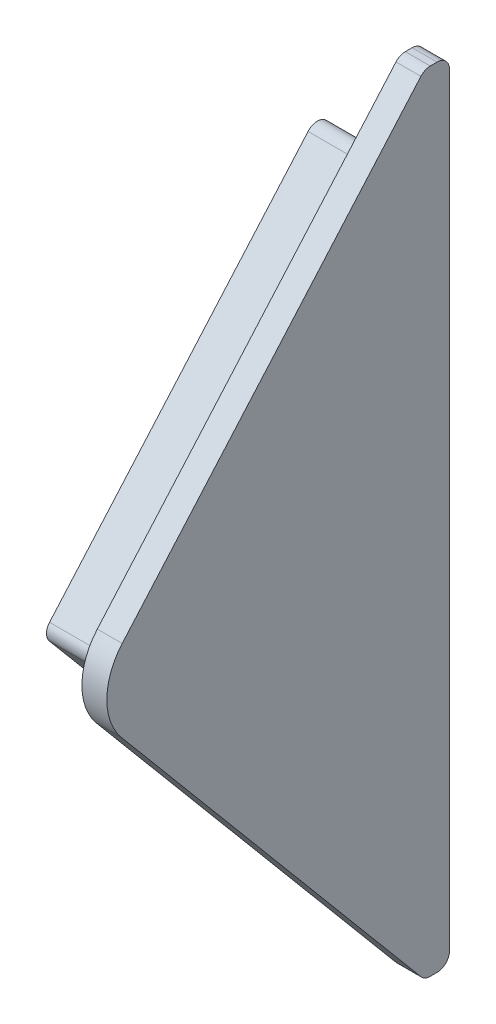
SolidWorks part; units mm, degrees
ref_plane "Front Plane" through (0, 0, 0) normal (0, 0, 1) x (1, 0, 0)
ref_plane "Top Plane" through (0, 0, 0) normal (0, 1, 0) x (1, 0, 0)
ref_plane "Right Plane" through (0, 0, 0) normal (1, 0, 0) x (0, 0, -1)
sketch "SideScreenView" plane through (0, 0, 0) normal (1, 0, 0) x (0, 0, -1)
  line L0 (0, 0) -> (0, 63.28)
  line L1 (0, 63.28) -> (21.5, 63.28)
  line L2 (21.5, 63.28) -> (21.5, 0)
  line L3 (21.5, 0) -> (0, 0)
  line L4 (0, 63.28) -> (-27.0861, 32.28)
  line L6 (18.75, 59.86) -> (15, 59.86)
  line L7 (15, 59.86) -> (15, 4.7)
  line L8 (15, 4.7) -> (18.75, 4.7)
  line L9 (18.75, 4.7) -> (18.75, 59.86)
  line L10 (11, 56.56) -> (15, 56.56)
  line L11 (15, 56.56) -> (15, 53.56)
  line L12 (15, 53.56) -> (11, 53.56)
  line L13 (11, 55.06) -> (11, 59.86) construction
  line L14 (11, 11) -> (15, 11)
  line L15 (15, 11) -> (15, 8)
  line L16 (15, 8) -> (11, 8)
  line L17 (11, 9.5) -> (11, 4.7) construction
  line L18 (11, 11) -> (11, 8)
  line L19 (11, 56.56) -> (11, 53.56)
  line L20 (15, 59.86) -> (11, 59.86) construction
  line L21 (18.75, 62.78) -> (21.5, 62.78)
  line L22 (21.5, 62.78) -> (21.5, 1.78)
  line L23 (21.5, 1.78) -> (18.75, 1.78)
  line L24 (18.75, 1.78) -> (18.75, 62.78)
  line L25 (11, 4.7) -> (15, 4.7) construction
  line L27 (-27.0861, 32.28) -> (0, 0)
  line L28 (1.5061, 61.9641) -> (-24.4532, 32.2537)
  line L29 (-24.4532, 32.2537) -> (1.5321, 1.2856)
  line L30 (11, 56.56) -> (0, 56.56) construction
  line L31 (11, 53.56) -> (0, 53.56) construction
  line L32 (11, 11) -> (0, 11) construction
  line L33 (11, 8) -> (0, 8) construction
  line L34 (0, 36.28) -> (4, 36.28)
  line L35 (0, 36.28) -> (0, 28.28)
  line L36 (4, 36.28) -> (4, 28.28)
  line L37 (0, 28.28) -> (4, 28.28)
  line L38 (0, 32.28) -> (15, 32.28) construction
  line L39 (4, 28.28) -> (4, 11) construction
  line L40 (4, 21.78) -> (9, 21.78)
  line L41 (4, 21.78) -> (4, 42.78)
  line L42 (9, 21.78) -> (9, 42.78)
  line L43 (4, 42.78) -> (9, 42.78)
  line L44 (4, 21.78) -> (9, 42.78) construction
  line L45 (9, 21.78) -> (4, 42.78) construction
  line L46 (4, 36.28) -> (9, 36.28)
  line L47 (9, 36.28) -> (9, 28.28)
  line L48 (9, 28.28) -> (4, 28.28)
  line L49 (9, 42.78) -> (9, 53.56) construction
  line L52 (0, 0) -> (21.5, 0)
  point P26 (18.75, 32.28)
  point P28 (18.75, 32.28)
  point P39 (6.5, 32.28)
  dimension "D3" = 55.16
  dimension "D4" = 3
  dimension "D5" = 4.8
  dimension "D6" = 4
  dimension "D7" = 61
  dimension "D8" = 6.5
  dimension "D9" = 8
  dimension "ThisArbitrary" = 2.75
  dimension "D10" = 4
  dimension "D11" = 40
  dimension "D12" = 8
  dimension "D13" = 2
  dimension "D14" = 2
  dimension "D16" = 0.5
  dimension "D19" = 21
  dimension "D20" = 15.3379
  dimension "D21" = 5
sketch "SideButtonView" plane through (0, 0, 0) normal (1, 0, 0) x (0, 0, -1)
  line L0 (21.5, 0) -> (0, 0) construction
  line L1 (0, 0) -> (0, 63.28) construction
  line L2 (0, 63.28) -> (21.5, 63.28) construction
  line L3 (21.5, 63.28) -> (21.5, 0) construction
  line L4 (21.5, 0) -> (0, 0)
  line L5 (0, 0) -> (0, 63.28)
  line L6 (0, 63.28) -> (21.5, 63.28)
  line L7 (21.5, 63.28) -> (21.5, 0)
  line L8 (15.7, 48.89) -> (30.7, 48.89)
  line L9 (30.7, 48.89) -> (30.7, 14.39)
  line L10 (30.7, 14.39) -> (15.7, 14.39)
  line L11 (15.7, 14.39) -> (15.7, 48.89)
  line L12 (15.7, 30.14) -> (15.7, 33.14)
  line L13 (15.7, 30.14) -> (11.2, 30.14)
  line L14 (15.7, 33.14) -> (11.2, 33.14)
  line L15 (11.2, 30.14) -> (11.2, 33.14)
  line L16 (11.2, 33.14) -> (30.7, 33.14) construction
  line L17 (11.2, 30.14) -> (11.2, 33.14)
  line L18 (11.2, 30.14) -> (9.5, 30.14)
  line L19 (11.2, 33.14) -> (9.5, 33.14)
  line L20 (9.5, 30.14) -> (9.5, 33.14)
  line L21 (6, 48.14) -> (9.5, 48.14)
  line L22 (6, 48.14) -> (6, 15.14)
  line L23 (9.5, 48.14) -> (9.5, 15.14)
  line L24 (6, 15.14) -> (9.5, 15.14)
  line L25 (6, 21.14) -> (6, 18.14)
  line L26 (6, 21.14) -> (2.5, 21.14)
  line L27 (6, 18.14) -> (2.5, 18.14)
  line L28 (2.5, 21.14) -> (2.5, 18.14)
  line L29 (6, 42.14) -> (6, 45.14)
  line L30 (6, 42.14) -> (2.5, 42.14)
  line L31 (6, 45.14) -> (2.5, 45.14)
  line L32 (2.5, 42.14) -> (2.5, 45.14)
  line L33 (2.5, 18.14) -> (9.5, 18.14) construction
  line L34 (2.5, 43.64) -> (2.5, 19.64) construction
  line L35 (6, 31.64) -> (2.5, 31.64) construction
  line L36 (2.5, 31.64) -> (0, 31.64) construction
  point P6 (9.5, 31.64)
  point P11 (15.7, 31.64)
  point P12 (9.5, 31.64)
  point P14 (15.7, 31.64)
  point P18 (11.2, 31.64)
  point P22 (11.2, 31.64)
  point P38 (2.5, 31.64)
  dimension "D1" = 34.5
  dimension "D2" = 15
  dimension "D3" = 19.5
  dimension "D4" = 7
  dimension "D5" = 8.7
  dimension "D6" = 24
  dimension "D7" = 3
  dimension "D8" = 2.5
  dimension "D9" = 3
  dimension "D10" = 3.5
  dimension "D11" = 33
sketch "Sketch3" plane through (0, 0, 0) normal (0, 1, 0) x (1, 0, 0)
  line L0 (-2, 21.5) -> (0, 21.5)
  dimension "D1" = 2
ref_plane "Plane1" through (0, 0, -21.5) normal (0, 0, 1) x (1, 0, 0)
sketch "FrontView" plane through (0, 0, -21.5) normal (0, 0, 1) x (1, 0, 0)
  line L0 (0, 63.28) -> (0, 0)
  line L1 (0, 63.28) -> (-133.94, 63.28)
  line L2 (0, 0) -> (-133.94, 0)
  line L3 (-133.94, 63.28) -> (-133.94, 0)
  line L4 (-0.5, 62.78) -> (-92.94, 62.78)
  line L5 (-0.5, 62.78) -> (-0.5, 1.78)
  line L6 (-92.94, 62.78) -> (-92.94, 1.78)
  line L7 (-0.5, 1.78) -> (-92.94, 1.78)
  line L8 (-15.882, 51.878) -> (-15.882, 12.682)
  line L9 (-7.9, 59.86) -> (-91.34, 59.86)
  line L10 (-7.9, 59.86) -> (-7.9, 4.7)
  line L11 (-7.9, 4.7) -> (-91.34, 4.7)
  line L12 (-91.34, 59.86) -> (-91.34, 4.7)
  line L17 (-15.882, 12.682) -> (-83.358, 12.682)
  line L18 (-83.358, 51.878) -> (-83.358, 12.682)
  line L19 (-15.882, 51.878) -> (-83.358, 51.878)
  line L20 (-97.94, 15.14) -> (-130.94, 48.14) construction
  line L21 (-97.94, 48.14) -> (-130.94, 48.14)
  line L22 (-97.94, 48.14) -> (-97.94, 15.14)
  line L23 (-97.94, 15.14) -> (-130.94, 15.14)
  line L24 (-130.94, 48.14) -> (-130.94, 15.14)
  line L25 (-126.44, 19.64) -> (-102.44, 43.64) construction
  line L26 (-133.94, 41.64) -> (-130.94, 41.64) construction
  line L27 (-133.94, 21.64) -> (-130.94, 21.64) construction
  line L28 (-133.94, 41.64) -> (-133.94, 21.64) construction
  line L49 (-86.12, 42.78) -> (-13.12, 42.78) construction
  line L50 (-86.12, 42.78) -> (-86.12, 21.78) construction
  line L51 (-13.12, 42.78) -> (-13.12, 21.78) construction
  line L52 (-86.12, 21.78) -> (-13.12, 21.78) construction
  line L53 (-49.62, 12.682) -> (-49.62, 21.78) construction
  line L54 (-13.12, 27.81) -> (0, 27.81)
  line L55 (-13.12, 27.81) -> (-13.12, 36.75)
  line L56 (-13.12, 36.75) -> (0, 36.75)
  line L57 (0, 27.81) -> (0, 36.75)
  line L58 (-88.12, 44.78) -> (-11.12, 44.78)
  line L59 (-11.12, 44.78) -> (-11.12, 19.78)
  line L60 (-88.12, 19.78) -> (-11.12, 19.78)
  line L61 (-88.12, 44.78) -> (-88.12, 19.78)
  line L62 (-97.94, 41.64) -> (-91.34, 41.64)
  line L63 (-97.94, 21.64) -> (-91.34, 21.64)
  line L70 (-117.44, 27.64) -> (-117.44, 35.64)
  line L71 (-117.44, 27.64) -> (-111.44, 27.64)
  line L72 (-117.44, 35.64) -> (-111.44, 35.64)
  line L73 (-111.44, 27.64) -> (-111.44, 35.64)
  line L74 (-117.44, 27.64) -> (-111.44, 35.64) construction
  line L75 (-117.44, 35.64) -> (-111.44, 27.64) construction
  line L76 (-117.44, 32.64) -> (-111.44, 32.64)
  line L77 (-117.44, 30.64) -> (-111.44, 30.64)
  line L78 (-114.44, 32.64) -> (-114.44, 30.64) construction
  circle A0 centre (-86.54, 55.06) radius 2.25
  circle A2 centre (-114.44, 31.64) radius 17.25 construction
  point P15 (-86.54, 55.06)
  point P18 (-12.7, 55.06)
  point P19 (-86.54, 9.5)
  point P20 (-12.7, 9.5)
  point P34 (-126.44, 43.64)
  point P35 (-102.44, 19.64)
  point P36 (-126.44, 19.64)
  point P37 (-102.44, 43.64)
  point P40 (-114.44, 31.64)
  point P41 (-114.44, 31.64)
  point P42 (-133.94, 31.64)
  point P45 (-13.12, 32.28)
  point P52 (-13.12, 32.28)
  point P94 (-114.44, 31.64)
  dimension "D8" = 4.5
  dimension "D9" = 2.25
  dimension "D13" = 34.5
  dimension "D1" = 92.44
  dimension "D2" = 4.8
  dimension "D3" = 4.8
  dimension "D4" = 4.8
  dimension "D5" = 4.8
  dimension "D6" = 1.6
  dimension "D7" = 83.44
  dimension "D10" = 0.5
  dimension "D11" = 24
  dimension "D12" = 24
  dimension "D14" = 5
  dimension "D15" = 73
  dimension "D16" = 20
  dimension "D17" = 3
  dimension "D18" = 21
  dimension "D19" = 6.03
  dimension "D20" = 2
  dimension "D22" = 8
  dimension "D23" = 6
  dimension "D24" = 2
sketch "Sketch5" plane through (0, 0, 0) normal (1, 0, 0) x (0, 0, -1)
  line L0 (21.5, 63.28) -> (21.5, 0) construction
  line L1 (21.5, 0) -> (0, 0) construction
  line L2 (0, 0) -> (0, 63.28) construction
  line L3 (0, 63.28) -> (21.5, 63.28) construction
  line L4 (21.5, 63.28) -> (21.5, 0)
  line L5 (21.5, 0) -> (0, 0)
  line L6 (0, 0) -> (0, 63.28)
  line L7 (0, 63.28) -> (21.5, 63.28)
  line L17 (0, 0) -> (21.5, 0) construction
  line L18 (0, 0) -> (21.5, 0)
sketch "Sketch31" plane through (0, 0, 0) normal (1, 0, 0) x (0, 0, -1)
  line L0 (0, 63.28) -> (-27.0861, 32.28) construction
  line L1 (-27.0861, 32.28) -> (0, 0) construction
  line L2 (-24.4532, 32.2537) -> (1.5321, 1.2856) construction
  line L3 (1.5061, 61.9641) -> (-24.4532, 32.2537) construction
  line L4 (0, 63.28) -> (-27.0861, 32.28)
  line L5 (-27.0861, 32.28) -> (0, 0)
  line L6 (-24.4532, 32.2537) -> (1.5321, 1.2856)
  line L7 (1.5061, 61.9641) -> (-24.4532, 32.2537)
  line L8 (0, 0) -> (0, 63.28) construction
  line L9 (0, 0) -> (0, 63.28)
sketch "Sketch32" plane through (0, 0, 0) normal (1, 0, 0) x (0, 0, -1)
  line L0 (0, 0) -> (0, 63.28) construction
  line L1 (-24.4532, 32.2537) -> (1.5321, 1.2856) construction
  line L2 (1.5061, 61.9641) -> (-24.4532, 32.2537) construction
  line L3 (0, 0) -> (0, 63.28)
  line L4 (-24.4532, 32.2537) -> (1.5321, 1.2856)
  line L5 (1.5061, 61.9641) -> (-24.4532, 32.2537)
  line L6 (1.9579, 61.5693) -> (-23.6634, 32.2458)
  line L7 (-23.6634, 32.2458) -> (1.9917, 1.6712)
  line L8 (-0.6, 0) -> (-0.6, 63.28)
  dimension "D1" = 0.6
extrude "Boss-Extrude1" add sketch "Sketch32" against normal blind 5 contours L7 L8 L6
sketch "Sketch33" plane through (0, 0, 0) normal (1, 0, 0) x (0, 0, -1)
  line L0 (0, 0) -> (0, 63.28) construction
  line L1 (0, 0) -> (2, 0)
  line L2 (-24.4532, 32.2537) -> (1.5321, 1.2856) construction
  line L3 (0, 0) -> (0, 3.1114)
  line L4 (-24.4532, 32.2537) -> (1.5321, 1.2856) construction
  line L5 (-24.4532, 32.2537) -> (0, 3.1114)
  line L6 (0, 63.28) -> (-27.0861, 32.28)
  line L7 (-27.0861, 32.28) -> (0, 0)
  line L8 (2, 0) -> (2, 63.28)
  line L9 (1.5061, 61.9641) -> (-24.4532, 32.2537) construction
  line L10 (0, 0) -> (0, 63.28) construction
  line L11 (0, 63.28) -> (2, 63.28)
  dimension "D2" = 3.1114
  dimension "D1" = 2
extrude "Boss-Extrude2" add sketch "Sketch33" along normal blind 2
fillet "Fillet1" radius 5 1 edges at (1, 32.28, 27.0861)
fillet "Fillet2" radius 1 3 edges at (-2.5, 4.7599, 0.6) (-2.5, 58.6418, 0.6) (-2.5, 32.2458, 23.6634)
fillet "Fillet3" radius 1 4 edges at (1, 0, 0) (1, 0, -2) (1, 63.28, 0) (1, 63.28, -2)
